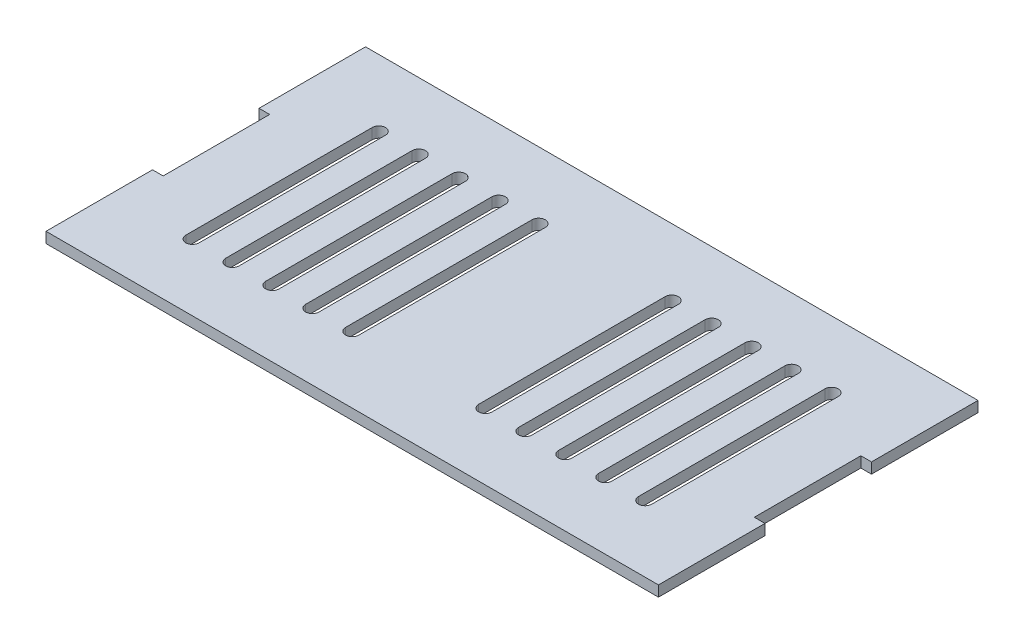
SolidWorks part; units mm, degrees
ref_plane "Front Plane" through (0, 0, 0) normal (0, 0, 1) x (1, 0, 0)
ref_plane "Top Plane" through (0, 0, 0) normal (0, 1, 0) x (1, 0, 0)
ref_plane "Right Plane" through (0, 0, 0) normal (1, 0, 0) x (0, 0, -1)
sketch "Sketch1" plane through (0, 0, 0) normal (0, 1, 0) x (1, 0, 0)
  line L0 (-115, 20) -> (-111, 20)
  line L1 (-115, -60) -> (115, -60)
  line L3 (-115, 60) -> (115, 60)
  line L4 (115, -60) -> (115, -20)
  line L5 (-115, -60) -> (115, 60) construction
  line L6 (-115, 60) -> (115, -60) construction
  line L7 (-115, -20) -> (-111, -20)
  line L8 (-115, -60) -> (-111, -60)
  line L9 (-111, 20) -> (-111, -20)
  line L10 (115, 20) -> (111, 20)
  line L11 (111, 20) -> (111, -20)
  line L12 (111, -20) -> (115, -20)
  line L13 (115, 20) -> (115, 60)
  line L15 (-115, -60) -> (-115, -20)
  line L23 (-115, 60) -> (-115, 20)
  point P0 (0, 0)
  dimension "D1" = 120
  dimension "D2" = 230
  dimension "D3" = 40
  dimension "D4" = 4
  dimension "D6" = 40
  dimension "D7" = 40
  dimension "D8" = 4
  dimension "D5" = 3
extrude "Boss-Extrude1" add sketch "Sketch1" along normal blind 4 contours L3 L23 L0 L9 L7 L15 L1 L4 L12 L11 L10 L13
sketch "Sketch2" plane through (0, 0, 0) normal (0, -1, 0) x (1, 0, 0)
  line L0 (-85, -35) -> (-85, 35) construction
  line L3 (-120.9553, 0) -> (127.2489, 0) construction
  line L4 (-87.5, -35) -> (-87.5, 35)
  line L5 (-82.5, -35) -> (-82.5, 35)
  line L6 (-115, -60) -> (-115, -20) construction
  line L7 (-70, -35) -> (-70, 35) construction
  line L8 (-72.5, -35) -> (-72.5, 35)
  line L9 (-67.5, -35) -> (-67.5, 35)
  line L10 (-55, -35) -> (-55, 35) construction
  line L11 (-57.5, -35) -> (-57.5, 35)
  line L12 (-52.5, -35) -> (-52.5, 35)
  line L13 (-40, -35) -> (-40, 35) construction
  line L14 (-42.5, -35) -> (-42.5, 35)
  line L15 (-37.5, -35) -> (-37.5, 35)
  line L16 (-25, -35) -> (-25, 35) construction
  line L17 (-27.5, -35) -> (-27.5, 35)
  line L18 (-22.5, -35) -> (-22.5, 35)
  line L22 (0, 67.8991) -> (0, -77.9483) construction
  line L23 (85, -35) -> (85, 35) construction
  line L24 (87.5, -35) -> (87.5, 35)
  line L25 (82.5, -35) -> (82.5, 35)
  line L26 (70, -35) -> (70, 35) construction
  line L27 (72.5, -35) -> (72.5, 35)
  line L28 (67.5, -35) -> (67.5, 35)
  line L29 (55, -35) -> (55, 35) construction
  line L30 (57.5, -35) -> (57.5, 35)
  line L31 (52.5, -35) -> (52.5, 35)
  line L32 (40, -35) -> (40, 35) construction
  line L33 (42.5, -35) -> (42.5, 35)
  line L34 (37.5, -35) -> (37.5, 35)
  line L35 (25, -35) -> (25, 35) construction
  line L36 (27.5, -35) -> (27.5, 35)
  line L37 (22.5, -35) -> (22.5, 35)
  line L50 (-10, -35) -> (-10, 35) construction
  line L51 (-12.5, -35) -> (-12.5, 35)
  line L52 (-7.5, -35) -> (-7.5, 35)
  line L53 (-10, -35) -> (-10, 35) construction
  line L54 (-12.5, -35) -> (-12.5, 35)
  line L55 (-7.5, -35) -> (-7.5, 35)
  arc A2 (-87.5, -35) -> (-82.5, -35) centre (-85, -35) ccw
  arc A3 (-82.5, 35) -> (-87.5, 35) centre (-85, 35) ccw
  arc A4 (-72.5, -35) -> (-67.5, -35) centre (-70, -35) ccw
  arc A5 (-67.5, 35) -> (-72.5, 35) centre (-70, 35) ccw
  arc A6 (-57.5, -35) -> (-52.5, -35) centre (-55, -35) ccw
  arc A7 (-52.5, 35) -> (-57.5, 35) centre (-55, 35) ccw
  arc A8 (-42.5, -35) -> (-37.5, -35) centre (-40, -35) ccw
  arc A9 (-37.5, 35) -> (-42.5, 35) centre (-40, 35) ccw
  arc A10 (-27.5, -35) -> (-22.5, -35) centre (-25, -35) ccw
  arc A11 (-22.5, 35) -> (-27.5, 35) centre (-25, 35) ccw
  arc A14 (87.5, -35) -> (82.5, -35) centre (85, -35) cw
  arc A15 (82.5, 35) -> (87.5, 35) centre (85, 35) cw
  arc A16 (72.5, -35) -> (67.5, -35) centre (70, -35) cw
  arc A17 (67.5, 35) -> (72.5, 35) centre (70, 35) cw
  arc A18 (57.5, -35) -> (52.5, -35) centre (55, -35) cw
  arc A19 (52.5, 35) -> (57.5, 35) centre (55, 35) cw
  arc A20 (42.5, -35) -> (37.5, -35) centre (40, -35) cw
  arc A21 (37.5, 35) -> (42.5, 35) centre (40, 35) cw
  arc A22 (27.5, -35) -> (22.5, -35) centre (25, -35) cw
  arc A23 (22.5, 35) -> (27.5, 35) centre (25, 35) cw
  arc A34 (-12.5, -35) -> (-7.5, -35) centre (-10, -35) ccw
  arc A35 (-7.5, 35) -> (-12.5, 35) centre (-10, 35) ccw
  point P2 (-85, 0)
  point P15 (-70, 0)
  point P22 (-55, 0)
  point P29 (-40, 0)
  point P36 (-25, 0)
  point P51 (85, 0)
  point P58 (70, 0)
  point P65 (55, 0)
  point P72 (40, 0)
  point P79 (25, 0)
  point P93 (-10, 0)
  point P100 (-10, 0)
  point P107 (-10, 0)
  point P114 (-10, 0)
  point P121 (-10, 0)
  dimension "D1" = 30
  dimension "D2" = 5
  dimension "D4" = 70
  dimension "D3" = 6
extrude "Cut-Extrude1" cut sketch "Sketch2" against normal blind 4
